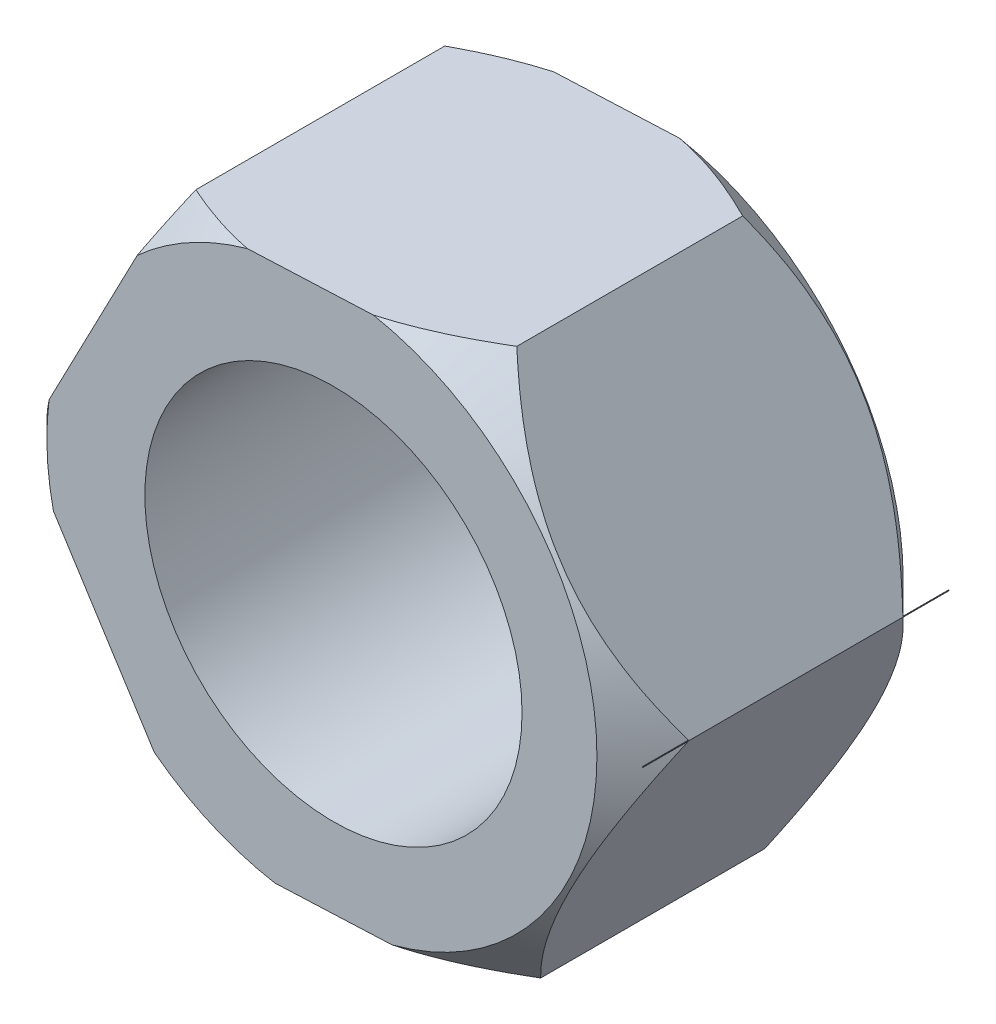
SolidWorks part; units mm, degrees
ref_plane "Front Plane" through (0, 0, 0) normal (0, 0, 1) x (1, 0, 0)
ref_plane "Top Plane" through (0, 0, 0) normal (0, 1, 0) x (1, 0, 0)
ref_plane "Right Plane" through (0, 0, 0) normal (1, 0, 0) x (0, 0, -1)
sketch "Sketch1" plane through (0, 0, 0) normal (0, 0, 1) x (1, 0, 0)
  line L1 (-0.1086, 0.1706) -> (-0.2021, -0.0087)
  line L2 (-0.2021, -0.0087) -> (-0.0935, -0.1794)
  line L3 (-0.0935, -0.1794) -> (0.1086, -0.1706)
  line L4 (0.1086, -0.1706) -> (0.2021, 0.0087)
  line L5 (0.2021, 0.0087) -> (0.0935, 0.1794)
  line L6 (0.0935, 0.1794) -> (-0.1086, 0.1706)
  circle A0 centre (0, 0) radius 0.1752 construction
  circle A1 centre (0, 0) radius 0.1232
  point P1 (-0.0075, 0.175)
  point P10 (0.0075, -0.175)
  dimension "D2" = 0.2463
  dimension "D1" = 0.35
extrude "Boss-Extrude2" add sketch "Sketch1" along normal blind 0.2
sketch "Sketch3" plane through (0, 0, 0) normal (0, 1, 0) x (1, 0, 0)
  line L0 (-0.0075, 0) -> (-0.0075, -50000) construction
  line L1 (0.0935, 0) -> (-0.1086, 0) construction
  line L2 (0.0935, -0.2) -> (-0.1086, -0.2) construction
  line L3 (-0.2021, -0.1) -> (49999.7979, -0.1) construction
  line L4 (-0.2021, -0.2) -> (-0.2021, 0) construction
  line L5 (0.2021, -0.2) -> (0.2021, 0) construction
  line L6 (0.1721, 0) -> (0.2021, 0)
  line L7 (0.2021, 0) -> (0.0935, 0) construction
  line L8 (0.2021, 0) -> (0.2021, -0.03)
  line L9 (0.2021, -0.03) -> (0.1721, 0)
  line L10 (0.2021, -0.2) -> (0.2021, -0.17)
  line L11 (0.1721, -0.2) -> (0.2021, -0.2)
  line L12 (0.2021, -0.17) -> (0.1721, -0.2)
  point P4 (-0.0075, 0)
  point P7 (-0.0075, -0.2)
  point P12 (-0.2021, -0.1)
  point P15 (0.2021, -0.1)
  dimension "D1" = 0.03
  dimension "D2" = 0.03
revolve "Cut-Revolve2" cut sketch "Sketch3" angle 360 about L0
